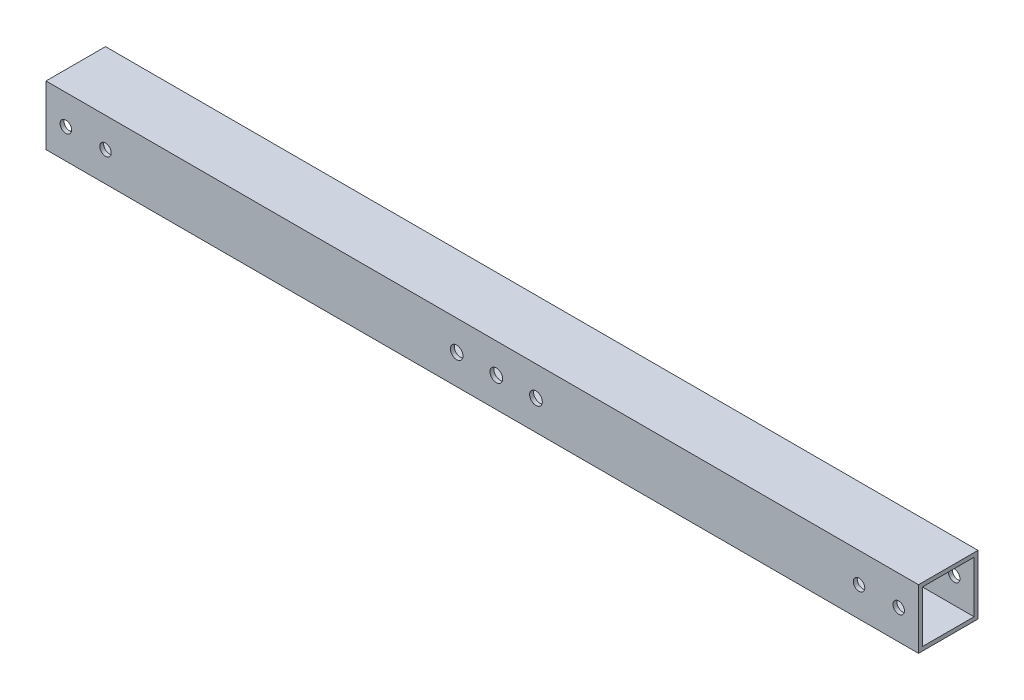
SolidWorks part; units mm, degrees
material "Thornel Mat VMA"
ref_plane "前视基准面" through (0, 0, 0) normal (0, 0, 1) x (1, 0, 0)
ref_plane "上视基准面" through (0, 0, 0) normal (0, 1, 0) x (1, 0, 0)
ref_plane "右视基准面" through (0, 0, 0) normal (1, 0, 0) x (0, 0, -1)
other "Configuration Table"
sketch "草图1" plane through (0, 0, 0) normal (1, 0, 0) x (0, 0, -1)
  line L0 (-6.5, -6.5) -> (-6.5, 6.5)
  line L1 (-7.5, -7.5) -> (7.5, -7.5)
  line L2 (-7.5, -7.5) -> (-7.5, 7.5)
  line L3 (-7.5, 7.5) -> (7.5, 7.5)
  line L4 (7.5, -7.5) -> (7.5, 7.5)
  line L5 (-7.5, -7.5) -> (7.5, 7.5) construction
  line L6 (-7.5, 7.5) -> (7.5, -7.5) construction
  line L7 (-6.5, 6.5) -> (6.5, 6.5)
  line L8 (6.5, -6.5) -> (6.5, 6.5)
  line L9 (-6.5, -6.5) -> (6.5, -6.5)
  point P0 (0, 0)
  dimension "D1" = 15
  dimension "D2" = 15
  dimension "D3" = 1
extrude "凸台-拉伸1" add sketch "草图1" along normal blind 220
sketch "草图2" plane through (0, 0, 7.5) normal (0, 0, 1) x (1, 0, 0)
  circle A0 centre (215, 0) radius 1.45 construction
  circle A1 centre (205, 0) radius 1.45 construction
  circle A2 centre (123.5452, 0) radius 1.6 construction
  circle A3 centre (113.5452, 0) radius 1.6 construction
  circle A4 centre (103.5452, 0) radius 1.6 construction
  circle A5 centre (15, 0) radius 1.45 construction
  circle A6 centre (5, 0) radius 1.45 construction
  circle A7 centre (215, 0) radius 1.45
  circle A8 centre (205, 0) radius 1.45
  circle A9 centre (123.5452, 0) radius 1.6
  circle A10 centre (113.5452, 0) radius 1.6
  circle A11 centre (103.5452, 0) radius 1.6
  circle A12 centre (15, 0) radius 1.45
  circle A13 centre (5, 0) radius 1.45
extrude "切除-拉伸1" cut sketch "草图2" against normal through all
